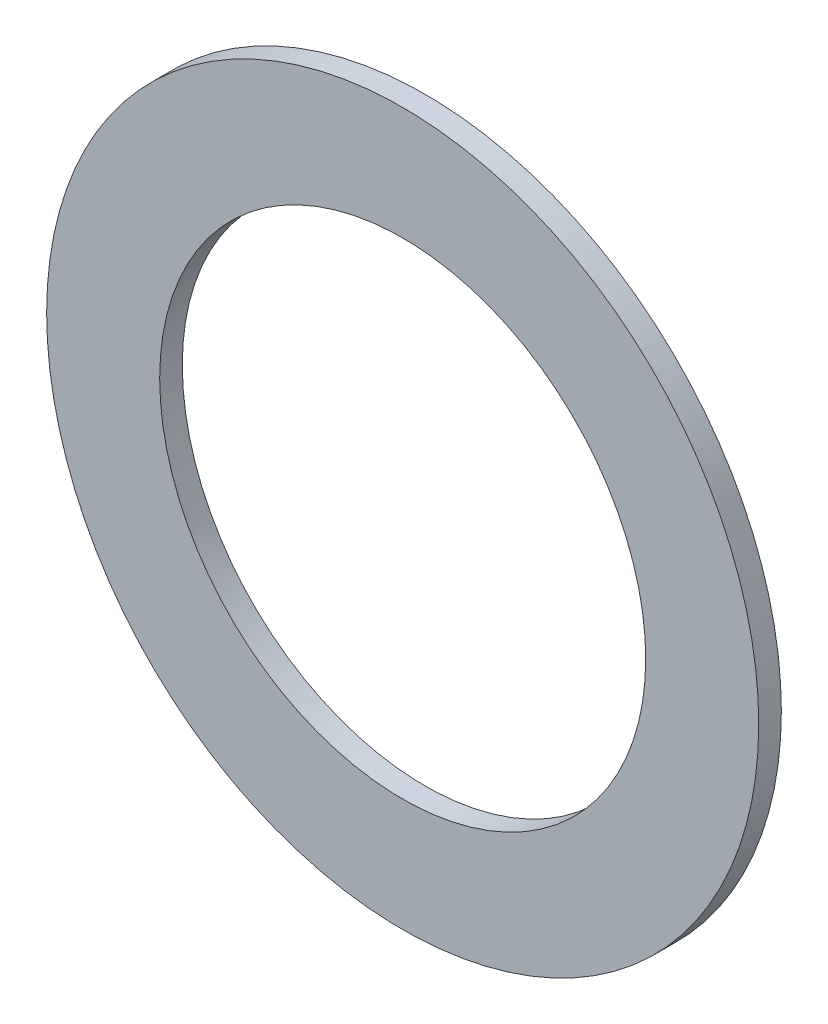
SolidWorks part; units mm, degrees
ref_plane "Front Plane" through (0, 0, 0) normal (0, 0, 1) x (1, 0, 0)
ref_plane "Top Plane" through (0, 0, 0) normal (0, 1, 0) x (1, 0, 0)
ref_plane "Right Plane" through (0, 0, 0) normal (1, 0, 0) x (0, 0, -1)
sketch "Sketch1" plane through (0, 0, 0) normal (0, 0, 1) x (1, 0, 0)
  circle A0 centre (0, 0) radius 10.75
  circle A1 centre (0, 0) radius 15.75
  dimension "D1" = 21.5
  dimension "D2" = 5
extrude "Boss-Extrude1" add sketch "Sketch1" along normal blind 1
